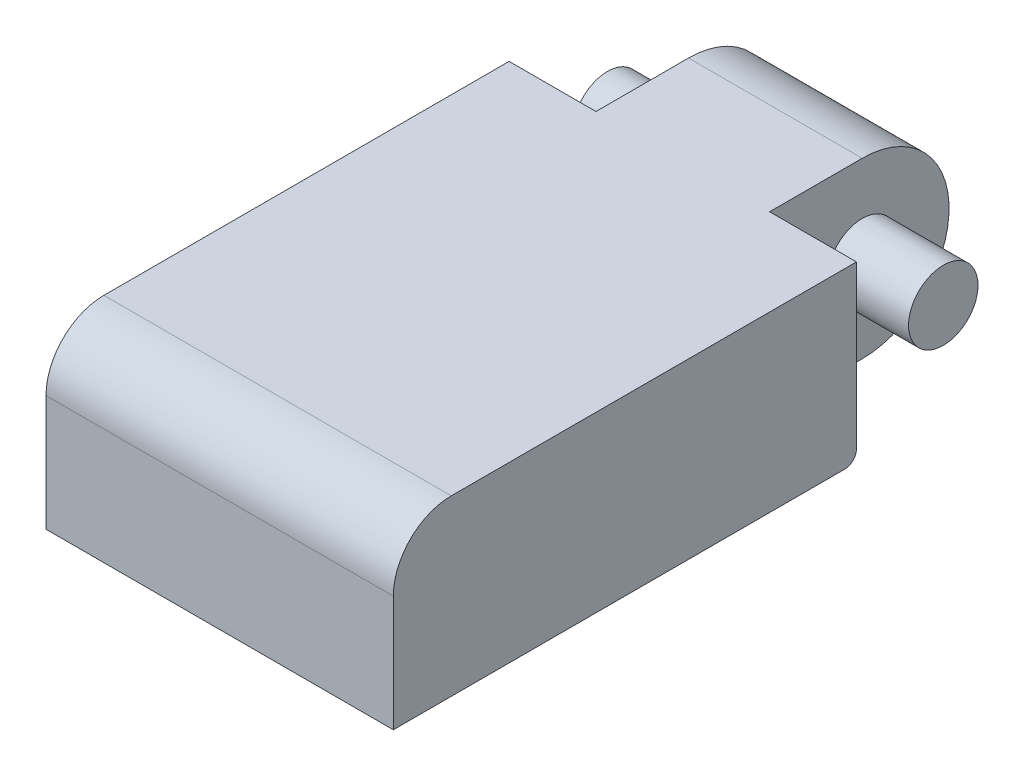
SolidWorks part; units mm, degrees
ref_plane "前视基准面" through (0, 0, 0) normal (0, 0, 1) x (1, 0, 0)
ref_plane "上视基准面" through (0, 0, 0) normal (0, 1, 0) x (1, 0, 0)
ref_plane "右视基准面" through (0, 0, 0) normal (1, 0, 0) x (0, 0, -1)
sketch "草图1" plane through (0, 0, 0) normal (0, 0, 1) x (1, 0, 0)
  line L1 (-15, 7.5) -> (15, 7.5)
  line L2 (-15, 7.5) -> (-15, -7.5)
  line L3 (-15, -7.5) -> (15, -7.5)
  line L4 (15, 7.5) -> (15, -7.5)
  line L5 (-15, 7.5) -> (15, -7.5) construction
  line L6 (-15, -7.5) -> (15, 7.5) construction
  point P0 (0, 0)
  dimension "D1" = 30
  dimension "D2" = 15
extrude "凸台-拉伸1" add sketch "草图1" along normal blind 40
sketch "草图6" plane through (0, 0, 0) normal (1, 0, 0) x (0, 0, -1)
  line L0 (0, 7.5) -> (8, 7.5)
  line L1 (8, -7.5) -> (0, -7.5)
  line L2 (0, 7.5) -> (0, -7.5)
  arc A0 (8, 7.5) -> (8, -7.5) centre (8, 0) cw
  dimension "D1" = 8
extrude "凸台-拉伸3" add sketch "草图6" along normal mid plane 15
sketch "草图7" plane through (7.5, 0, 0) normal (1, 0, 0) x (0, 0, -1)
  circle A0 centre (8, 0) radius 3
  dimension "D1" = 6
extrude "凸台-拉伸4" add sketch "草图7" along normal blind 7
mirror "镜向2" about plane through (0, 0, 0) normal (1, 0, 0) of "凸台-拉伸4"
fillet "圆角1" radius 5 1 edges at (0, 7.5, 40)
fillet "圆角2" radius 1 2 edges at (-11.25, -7.5, 0) (11.25, -7.5, 0)
